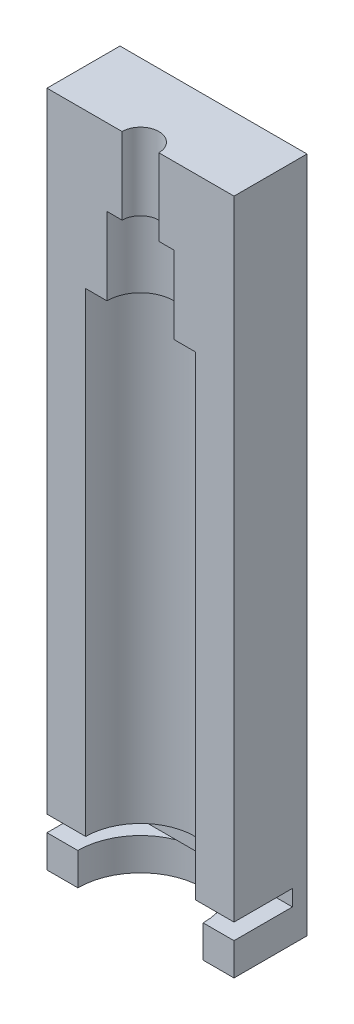
SolidWorks part; units mm, degrees
ref_plane "Front Plane" through (0, 0, 0) normal (1, 0, 0) x (0, 1, 0)
ref_plane "Top Plane" through (0, 0, 0) normal (0, 0, 1) x (0, 1, 0)
ref_plane "Right Plane" through (0, 0, 0) normal (0, 1, 0) x (-1, 0, 0)
sketch "Sketch1" plane through (0, 0, 0) normal (0, 0, 1) x (0, 1, 0)
  line L1 (-75, -150) -> (75, -150)
  line L2 (-75, -150) -> (-75, 150)
  line L3 (-75, 150) -> (75, 150)
  line L4 (75, -150) -> (75, 150)
  line L5 (-75, -150) -> (75, 150) construction
  line L6 (-75, 150) -> (75, -150) construction
  point P0 (0, 0)
  dimension "D1" = 300
  dimension "D2" = 150
extrude "Boss-Extrude1" add sketch "Sketch1" along normal blind 10
sketch "flange slit" plane through (0, 0, 10) normal (0, 0, 1) x (1, 0, 0)
  line L0 (0, 75) -> (0, -75) construction
  line L1 (150, 75) -> (-150, 75) construction
  line L2 (-150, -75) -> (150, -75) construction
  line L3 (-124, 0) -> (150, 0) construction
  line L5 (150, -75) -> (150, 75) construction
  line L6 (-70.7884, -70.5711) -> (-70.7884, -68.3711) construction
  line L7 (-150, 75) -> (-124, 75) construction
  line L9 (-150, -75) -> (-124, -75) construction
  line L11 (-70.7884, -70.5711) -> (-70.7884, -69.4711) construction
  line L12 (-150.383, -68.3711) -> (-124.383, -68.3711)
  line L13 (-150.383, -68.3711) -> (-150.383, -70.5711)
  line L14 (-150.383, -70.5711) -> (-124.383, -70.5711)
  line L19 (-124.383, -68.3711) -> (-124.383, -70.5711)
  line L20 (-150.383, -68.3711) -> (-124.383, -70.5711) construction
  line L21 (-150.383, -70.5711) -> (-124.383, -68.3711) construction
  line L26 (-70.7884, -69.4711) -> (-150.383, -69.4711) construction
  point P8 (-137.383, -69.4711)
  point P23 (0, 0)
  point P24 (-137.383, -62.6992)
  point P26 (-136.9874, -65.276)
  point P27 (-137.383, -69.4711)
  dimension "D1" = 26
  dimension "D2" = 2.2
extrude "Flange Slot" cut sketch "flange slit" against normal blind 8
sketch "Sketch3" plane through (0, 0, 10) normal (0, 0, 1) x (1, 0, 0)
  line L0 (-150, -75) -> (150, -75) construction
  line L1 (-150, 75) -> (-124.383, 75) construction
  line L2 (-150, 75) -> (-150, -75) construction
  line L3 (-150, -75) -> (-124.383, -75) construction
  line L4 (-124.383, 75) -> (-124.383, -75) construction
  line L5 (-150, 75) -> (-124.383, -75) construction
  line L6 (-150, -75) -> (-124.383, 75) construction
  line L7 (-124.383, -70.5711) -> (-124.383, -68.3711) construction
  line L8 (-124.383, -68.3711) -> (-150, -68.3711) construction
  line L9 (-144.6915, -68.3711) -> (-129.6915, -68.3711)
  line L10 (-144.6915, -68.3711) -> (-144.6915, -3.3711)
  line L11 (-144.6915, -3.3711) -> (-129.6915, -3.3711)
  line L12 (-129.6915, -68.3711) -> (-129.6915, -3.3711)
  line L13 (-144.6915, -68.3711) -> (-129.6915, -3.3711) construction
  line L14 (-144.6915, -3.3711) -> (-129.6915, -68.3711) construction
  line L15 (-137.1915, 75) -> (-137.1915, -68.3711) construction
  line L16 (-137.1915, -3.3711) -> (-137.1915, -68.3711)
  line L18 (-144.6915, -3.3711) -> (-137.1915, -3.3711)
  line L19 (-144.6915, -3.3711) -> (-144.6915, -68.3711)
  line L20 (-144.6915, -68.3711) -> (-137.1915, -68.3711)
  line L21 (-137.1915, -3.3711) -> (-137.1915, -68.3711)
  line L22 (-144.6915, -3.3711) -> (-137.1915, -68.3711) construction
  line L23 (-144.6915, -68.3711) -> (-137.1915, -3.3711) construction
  point P4 (-137.1915, 0)
  point P14 (-137.1915, -35.8711)
  point P23 (-140.9415, -35.8711)
  dimension "D1" = 65
  dimension "D2" = 15
revolve "Syringe Body Slot" cut sketch "Sketch3" angle 360 about L15
sketch "Sketch6" plane through (0, 0, 10) normal (0, 0, 1) x (0, -1, 0)
  line L0 (75, 150) -> (-75, 150) construction
  line L1 (-75, -150) -> (-17.7492, -150)
  line L2 (-75, -150) -> (-75, 150)
  line L3 (-75, 150) -> (-17.7492, 150)
  line L4 (-17.7492, -150) -> (-17.7492, 150)
  line L5 (-75, -150) -> (-17.7492, 150) construction
  line L6 (-75, 150) -> (-17.7492, -150) construction
  point P4 (-46.3746, 0)
extrude "Cut-Extrude2" cut sketch "Sketch6" against normal through all
sketch "Sketch7" plane through (0, 0, 10) normal (0, 0, 1) x (1, 0, 0)
  line L0 (-150, -70.5711) -> (-124.383, -70.5711) construction
  line L1 (-137.1915, -70.5711) -> (-145.7782, -70.5711)
  line L2 (-137.1915, -70.5711) -> (-137.1915, -75)
  line L3 (-137.1915, -75) -> (-145.7782, -75)
  line L4 (-145.7782, -70.5711) -> (-145.7782, -75)
  line L5 (-137.1915, -70.5711) -> (-145.7782, -75) construction
  line L6 (-137.1915, -75) -> (-145.7782, -70.5711) construction
  line L7 (-150, -75) -> (150, -75) construction
  point P4 (-141.4849, -72.7855)
revolve "Plunger Slot" cut sketch "Sketch7" angle 360 about L2
sketch "Sketch8" plane through (0, 0, 10) normal (0, 0, 1) x (1, 0, 0)
  line L0 (-144.6915, -3.3711) -> (-129.6915, -3.3711) construction
  line L5 (-150, 17.7492) -> (150, 17.7492) construction
  line L11 (-137.1915, -3.3711) -> (-141.7915, -3.3711)
  line L12 (-137.1915, -3.3711) -> (-137.1915, 4.6289)
  line L13 (-139.7097, 7.2365) -> (-141.7915, 7.2365)
  line L14 (-141.7915, -3.3711) -> (-141.7915, 7.2365)
  line L16 (-137.1915, 4.6289) -> (-137.1915, 17.7492)
  line L17 (-137.1915, 17.7492) -> (-139.7097, 17.7492)
  line L18 (-139.7097, 7.2365) -> (-139.7097, 17.7492)
  dimension "D1" = 8
  dimension "D2" = 4.6
  dimension "D3" = 3.625
revolve "Cut-Revolve1" cut sketch "Sketch8" angle 360 about L12
sketch "Sketch15" plane through (0, 0, 10) normal (0, 0, 1) x (1, 0, 0)
  line L0 (-128.6048, -75) -> (150, -75) construction
  line L1 (-124.383, -75) -> (150, -75)
  line L2 (-124.383, -75) -> (-124.383, 17.7492)
  line L3 (-124.383, 17.7492) -> (150, 17.7492)
  line L4 (150, -75) -> (150, 17.7492)
extrude "Cut-Extrude3" cut sketch "Sketch15" against normal through all both and the other way through all
